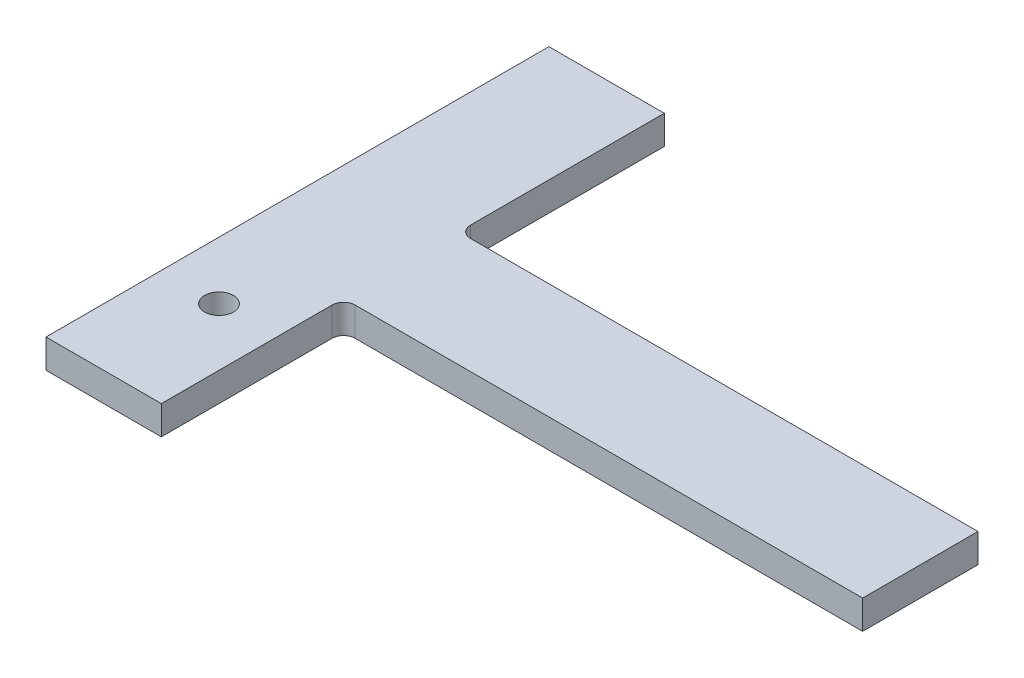
SolidWorks part; units mm, degrees
ref_plane "Front Plane" through (0, 0, 0) normal (0, 0, 1) x (1, 0, 0)
ref_plane "Top Plane" through (0, 0, 0) normal (0, 1, 0) x (1, 0, 0)
ref_plane "Right Plane" through (0, 0, 0) normal (1, 0, 0) x (0, 0, -1)
sketch "Sketch2" plane through (0, 0, 0) normal (0, 1, 0) x (1, 0, 0)
  line L0 (-16.6255, 1.4547) -> (-16.6255, -38.6773)
  line L1 (-42.0255, 72.0667) -> (-16.6255, 72.0667)
  line L2 (-42.0255, 72.0667) -> (-42.0255, -38.6773)
  line L3 (-42.0255, -38.6773) -> (-16.6255, -38.6773)
  line L4 (-16.6255, 72.0667) -> (-16.6255, 26.8547)
  line L5 (-16.6255, 26.8547) -> (97.6745, 26.8547)
  line L7 (-16.6255, 1.4547) -> (97.6745, 1.4547)
  line L8 (97.6745, 26.8547) -> (97.6745, 1.4547)
  circle A0 centre (-29.3255, -13.2773) radius 3.175
  dimension "D4" = 6.35
  dimension "D1" = 25.4
  dimension "D2" = 114.3
  dimension "D3" = 25.4
  dimension "D5" = 25.4
  dimension "D7" = 12.7
  dimension "D8" = 40.132
  dimension "D6" = 110.744
extrude "Boss-Extrude1" add sketch "Sketch2" along normal blind 6.35
fillet "Fillet1" radius 2.54 2 edges at (-16.6255, 3.175, -1.4547) (-16.6255, 3.175, -26.8547)
equation "\"t\"= 0.25in"
equation "\"width\"= 1in"
equation "\"D1@Sketch2\"=\"width\""
equation "\"D3@Sketch2\"=\"width\""
equation "\"D7@Sketch2\"=\"width\"/2"
equation "\"D1@Boss-Extrude1\"=\"t\""
